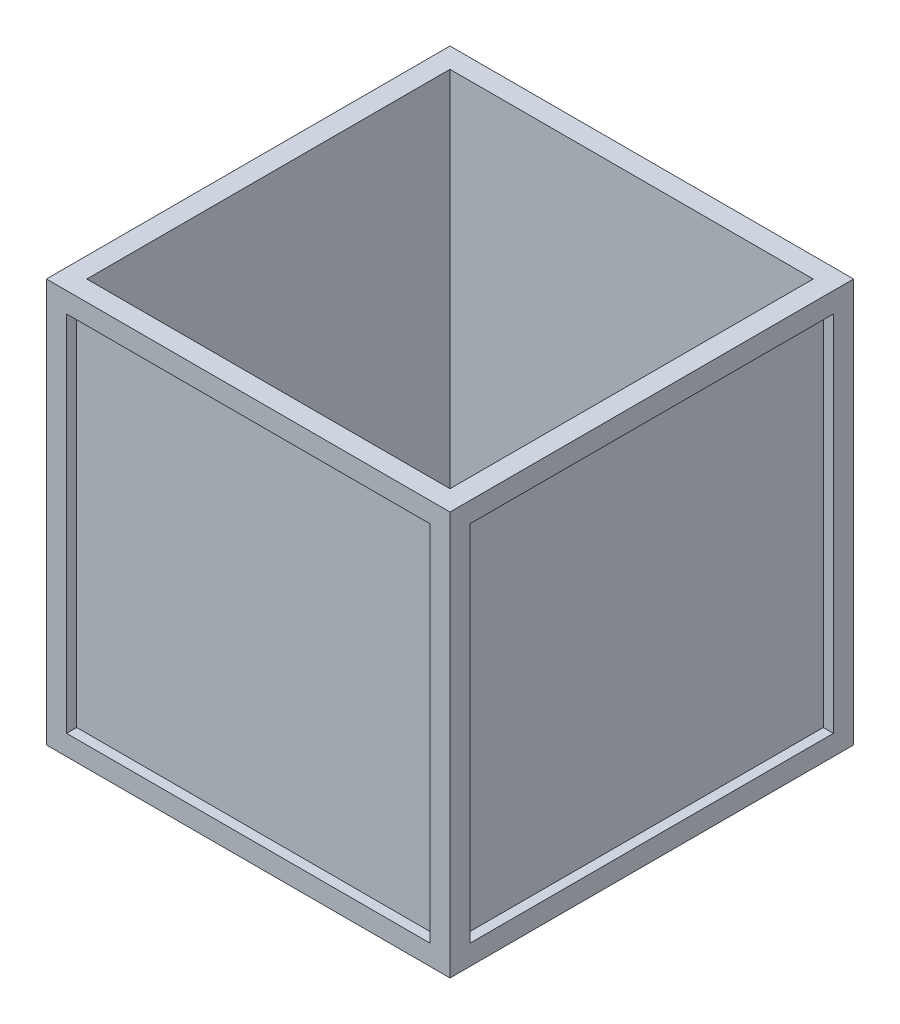
SolidWorks part; units mm, degrees
ref_plane "Front Plane" through (0, 0, 0) normal (0, 0, 1) x (1, 0, 0)
ref_plane "Top Plane" through (0, 0, 0) normal (0, 1, 0) x (1, 0, 0)
ref_plane "Right Plane" through (0, 0, 0) normal (1, 0, 0) x (0, 0, -1)
sketch "Sketch1" plane through (0, 0, 0) normal (0, 1, 0) x (1, 0, 0)
  line L1 (-25.4, -25.4) -> (25.4, -25.4)
  line L2 (-25.4, -25.4) -> (-25.4, 25.4)
  line L3 (-25.4, 25.4) -> (25.4, 25.4)
  line L4 (25.4, -25.4) -> (25.4, 25.4)
  line L5 (-25.4, -25.4) -> (25.4, 25.4) construction
  line L6 (-25.4, 25.4) -> (25.4, -25.4) construction
  point P0 (0, 0)
  dimension "D1" = 50.8
  dimension "D2" = 50.8
extrude "Boss-Extrude1" add sketch "Sketch1" along normal blind 50.8
shell "Shell1" thickness 2.54
sketch "Sketch2" plane through (0, 0, 25.4) normal (0, 0, 1) x (1, 0, 0)
  line L0 (-25.4, 50.8) -> (25.4, 50.8) construction
  line L1 (-22.86, 2.54) -> (22.86, 2.54)
  line L2 (-22.86, 2.54) -> (-22.86, 48.26)
  line L3 (-22.86, 48.26) -> (22.86, 48.26)
  line L4 (22.86, 2.54) -> (22.86, 48.26)
  line L5 (-22.86, 2.54) -> (22.86, 48.26) construction
  line L6 (-22.86, 48.26) -> (22.86, 2.54) construction
  line L7 (-25.4, 0) -> (25.4, 0) construction
  line L8 (-25.4, 50.8) -> (-25.4, 0) construction
  line L9 (25.4, 50.8) -> (25.4, 0) construction
  point P0 (0, 25.4)
  dimension "D1" = 2.54
  dimension "D2" = 2.54
  dimension "D3" = 2.54
  dimension "D4" = 2.54
extrude "Cut-Extrude1" cut sketch "Sketch2" against normal blind 1.27
sketch "Sketch3" plane through (25.4, 0, 0) normal (1, 0, 0) x (0, 0, -1)
  line L0 (-25.4, 50.8) -> (25.4, 50.8) construction
  line L1 (-22.86, 2.54) -> (22.86, 2.54)
  line L2 (-22.86, 2.54) -> (-22.86, 48.26)
  line L3 (-22.86, 48.26) -> (22.86, 48.26)
  line L4 (22.86, 2.54) -> (22.86, 48.26)
  line L5 (-22.86, 2.54) -> (22.86, 48.26) construction
  line L6 (-22.86, 48.26) -> (22.86, 2.54) construction
  line L7 (-25.4, 50.8) -> (-25.4, 0) construction
  line L8 (-25.4, 0) -> (25.4, 0) construction
  line L9 (25.4, 50.8) -> (25.4, 0) construction
  point P0 (0, 25.4)
  dimension "D1" = 2.54
  dimension "D2" = 2.54
  dimension "D3" = 2.54
  dimension "D4" = 2.54
extrude "Cut-Extrude2" cut sketch "Sketch3" against normal blind 1.27
sketch "Sketch4" plane through (0, 0, -25.4) normal (0, 0, -1) x (-1, 0, 0)
  line L0 (-25.4, 50.8) -> (25.4, 50.8) construction
  line L1 (-22.86, 2.54) -> (22.86, 2.54)
  line L2 (-22.86, 2.54) -> (-22.86, 48.26)
  line L3 (-22.86, 48.26) -> (22.86, 48.26)
  line L4 (22.86, 2.54) -> (22.86, 48.26)
  line L5 (-22.86, 2.54) -> (22.86, 48.26) construction
  line L6 (-22.86, 48.26) -> (22.86, 2.54) construction
  line L7 (-25.4, 0) -> (25.4, 0) construction
  line L8 (25.4, 50.8) -> (25.4, 0) construction
  line L9 (-25.4, 50.8) -> (-25.4, 0) construction
  point P0 (0, 25.4)
  dimension "D1" = 2.54
  dimension "D2" = 2.54
  dimension "D3" = 2.54
  dimension "D4" = 2.54
extrude "Cut-Extrude3" cut sketch "Sketch4" against normal blind 1.27
sketch "Sketch5" plane through (-25.4, 0, 0) normal (-1, 0, 0) x (0, 0, 1)
  line L0 (-25.4, 50.8) -> (25.4, 50.8) construction
  line L1 (-22.86, 2.54) -> (22.86, 2.54)
  line L2 (-22.86, 2.54) -> (-22.86, 48.26)
  line L3 (-22.86, 48.26) -> (22.86, 48.26)
  line L4 (22.86, 2.54) -> (22.86, 48.26)
  line L5 (-22.86, 2.54) -> (22.86, 48.26) construction
  line L6 (-22.86, 48.26) -> (22.86, 2.54) construction
  line L7 (25.4, 50.8) -> (25.4, 0) construction
  line L8 (-25.4, 0) -> (25.4, 0) construction
  line L9 (-25.4, 50.8) -> (-25.4, 0) construction
  point P0 (0, 25.4)
  dimension "D1" = 2.54
  dimension "D2" = 2.54
  dimension "D3" = 2.54
  dimension "D4" = 2.54
extrude "Cut-Extrude4" cut sketch "Sketch5" against normal blind 1.27
